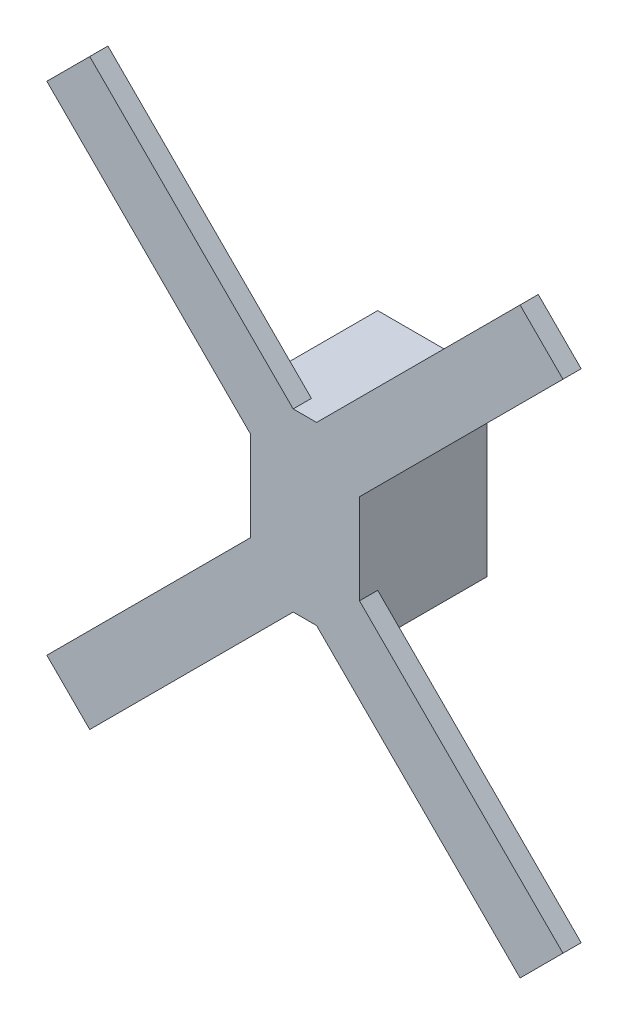
SolidWorks part; units mm, degrees
ref_plane "Alzado" through (0, 0, 0) normal (0, 0, 1) x (1, 0, 0)
ref_plane "Planta" through (0, 0, 0) normal (0, 1, 0) x (1, 0, 0)
ref_plane "Vista lateral" through (0, 0, 0) normal (1, 0, 0) x (0, 0, -1)
sketch "Croquis1" plane through (0, 0, 0) normal (0, 0, 1) x (1, 0, 0)
  line L1 (-24.2653, -2.502) -> (-10.2653, -2.502)
  line L2 (-24.2653, -2.502) -> (-24.2653, -27.502)
  line L3 (-24.2653, -27.502) -> (-10.2653, -27.502)
  line L4 (-10.2653, -2.502) -> (-10.2653, -27.502)
  line L8 (-26.2653, -2.502) -> (-26.2653, -29.502)
  line L9 (-26.2653, -29.502) -> (-10.2653, -29.502)
  line L10 (-10.2653, -29.502) -> (-8.2653, -29.502)
  line L11 (-8.2653, -29.502) -> (-8.2653, -27.502)
  line L12 (-8.2653, -27.502) -> (-8.2653, -0.502)
  line L13 (-8.2653, -0.502) -> (-24.2653, -0.502)
  line L14 (-26.2653, -2.502) -> (-26.2653, -0.502)
  line L15 (-26.2653, -0.502) -> (-24.2653, -0.502)
extrude "Saliente-Extruir3" add sketch "Croquis1" along normal blind 21
sketch "Croquis3" plane through (0, 0, 21) normal (0, 0, 1) x (1, 0, 0)
  line L1 (-24.2653, -2.502) -> (-10.2653, -2.502)
  line L2 (-24.2653, -2.502) -> (-24.2653, -27.502)
  line L3 (-24.2653, -27.502) -> (-10.2653, -27.502)
  line L4 (-10.2653, -2.502) -> (-10.2653, -27.502)
extrude "Saliente-Extruir4" add sketch "Croquis3" against normal blind 2
sketch "Croquis4" plane through (0, 0, 21) normal (0, 0, 1) x (1, 0, 0)
  line L3 (-56.2653, 29.498) -> (-52.7297, 33.0335)
  line L4 (-56.2653, 29.498) -> (-59.8008, 25.9625)
  line L5 (-59.8008, 25.9625) -> (-26.2653, -7.5731)
  line L6 (-26.2653, -0.502) -> (-26.2653, -29.502) construction
  line L7 (-52.7297, 33.0335) -> (-19.1942, -0.502)
  line L8 (-8.2653, -0.502) -> (-26.2653, -0.502) construction
  line L9 (-26.2653, -7.5731) -> (-26.2653, -0.502)
  line L10 (-26.2653, -0.502) -> (-19.1942, -0.502)
  line L14 (21.7347, 29.498) -> (25.2703, 25.9625)
  line L15 (21.7347, 29.498) -> (18.1992, 33.0335)
  line L16 (18.1992, 33.0335) -> (-15.3363, -0.502)
  line L17 (-15.3363, -0.502) -> (-8.2653, -0.502)
  line L18 (25.2703, 25.9625) -> (-8.2653, -7.5731)
  line L19 (-8.2653, -29.502) -> (-8.2653, -0.502) construction
  line L20 (-8.2653, -7.5731) -> (-8.2653, -0.502)
  line L24 (25.2703, -55.9665) -> (21.7347, -59.502)
  line L25 (18.1992, -63.0375) -> (21.7347, -59.502)
  line L26 (18.1992, -63.0375) -> (-15.3363, -29.502)
  line L27 (-26.2653, -29.502) -> (-8.2653, -29.502) construction
  line L28 (-15.3363, -29.502) -> (-8.2653, -29.502)
  line L29 (25.2703, -55.9665) -> (-8.2653, -22.4309)
  line L30 (-8.2653, -22.4309) -> (-8.2653, -29.502)
  line L33 (-56.2653, -59.502) -> (-59.8008, -55.9665)
  line L34 (-59.8008, -55.9665) -> (-26.2653, -22.4309)
  line L36 (-56.2653, -59.502) -> (-52.7297, -63.0375)
  line L38 (-19.1942, -29.502) -> (-52.7297, -63.0375)
  line L39 (-26.2653, -22.4309) -> (-26.2653, -29.502)
  line L40 (-19.1942, -29.502) -> (-26.2653, -29.502)
extrude "Saliente-Extruir5" add sketch "Croquis4" against normal blind 3
